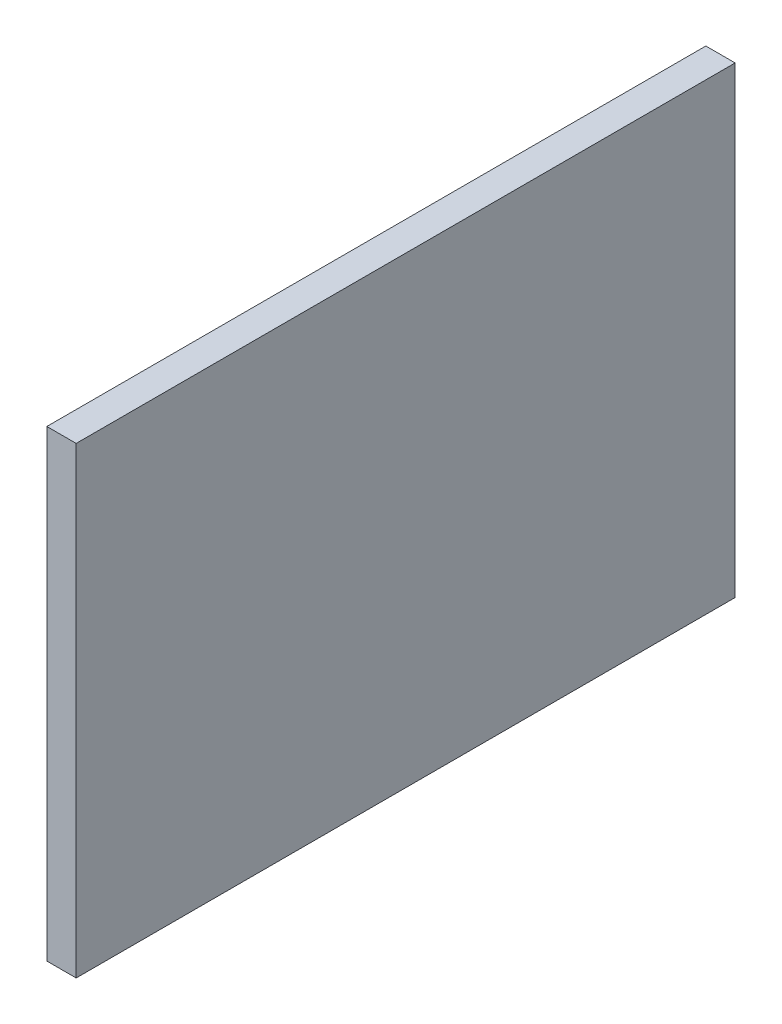
SolidWorks part; units mm, degrees
ref_plane "Front Plane" through (0, 0, 0) normal (0, 0, 1) x (1, 0, 0)
ref_plane "Top Plane" through (0, 0, 0) normal (0, 1, 0) x (1, 0, 0)
ref_plane "Right Plane" through (0, 0, 0) normal (1, 0, 0) x (0, 0, -1)
sketch "Sketch1" plane through (0, 0, 0) normal (1, 0, 0) x (0, 0, -1)
  line L1 (0, 0) -> (427, 0)
  line L2 (0, 0) -> (0, 300)
  line L3 (0, 300) -> (427, 300)
  line L4 (427, 0) -> (427, 300)
  dimension "D1" = 427
  dimension "D2" = 300
extrude "Boss-Extrude1" add sketch "Sketch1" along normal blind 19
